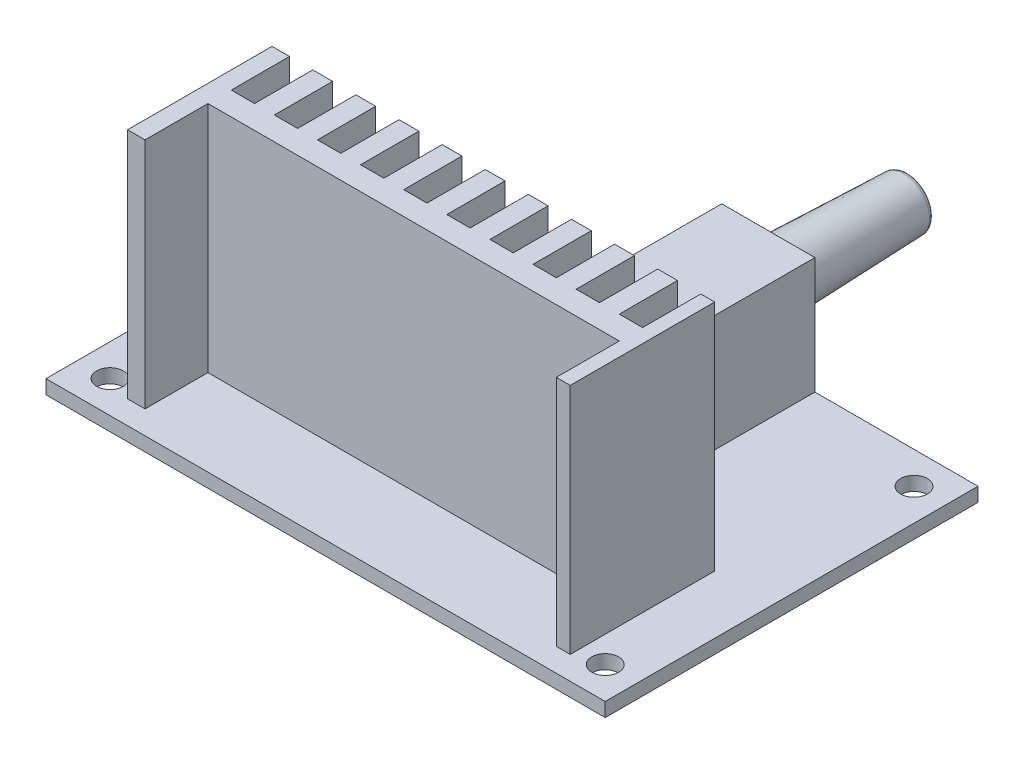
SolidWorks part; units mm, degrees
ref_plane "Front Plane" through (0, 0, 0) normal (0, 0, 1) x (1, 0, 0)
ref_plane "Top Plane" through (0, 0, 0) normal (0, 1, 0) x (1, 0, 0)
ref_plane "Right Plane" through (0, 0, 0) normal (1, 0, 0) x (0, 0, -1)
sketch "Sketch1" plane through (0, 0, 0) normal (0, 1, 0) x (1, 0, 0)
  line L1 (-30.48, -20.32) -> (30.48, -20.32)
  line L2 (-30.48, -20.32) -> (-30.48, 20.32)
  line L3 (-30.48, 20.32) -> (30.48, 20.32)
  line L4 (30.48, -20.32) -> (30.48, 20.32)
  line L5 (-30.48, -20.32) -> (30.48, 20.32) construction
  line L6 (-30.48, 20.32) -> (30.48, -20.32) construction
  point P0 (0, 0)
  dimension "D1" = 40.64
  dimension "D2" = 60.96
extrude "Boss-Extrude1" add sketch "Sketch1" along normal blind 1.524
sketch "Sketch2" plane through (0, 1.524, 0) normal (0, 1, 0) x (1, 0, 0)
  line L0 (-14.985, -2.032) -> (-14.985, -8.382)
  line L1 (-24.13, -17.78) -> (-22.225, -17.78)
  line L2 (-24.13, -17.78) -> (-24.13, -2.032)
  line L3 (-24.13, -2.032) -> (-22.225, -2.032)
  line L4 (24.13, -17.78) -> (24.13, -2.032)
  line L5 (-24.13, -17.78) -> (24.13, -2.032) construction
  line L6 (-24.13, -2.032) -> (24.13, -17.78) construction
  line L8 (-22.225, -2.032) -> (-22.225, -8.382)
  line L9 (-22.225, -8.382) -> (-19.685, -8.382)
  line L10 (-19.685, -2.032) -> (-19.685, -8.382)
  line L11 (-22.225, -2.032) -> (-19.685, -8.382) construction
  line L12 (-22.225, -8.382) -> (-19.685, -2.032) construction
  line L13 (-17.525, -8.382) -> (-14.985, -8.382)
  line L14 (-17.525, -2.032) -> (-17.525, -8.382)
  line L15 (-10.285, -2.032) -> (-10.285, -8.382)
  line L16 (-12.825, -8.382) -> (-10.285, -8.382)
  line L17 (-12.825, -2.032) -> (-12.825, -8.382)
  line L18 (-5.585, -2.032) -> (-5.585, -8.382)
  line L19 (-8.125, -8.382) -> (-5.585, -8.382)
  line L20 (-8.125, -2.032) -> (-8.125, -8.382)
  line L21 (-0.885, -2.032) -> (-0.885, -8.382)
  line L22 (-3.425, -8.382) -> (-0.885, -8.382)
  line L23 (-3.425, -2.032) -> (-3.425, -8.382)
  line L24 (3.815, -2.032) -> (3.815, -8.382)
  line L25 (1.275, -8.382) -> (3.815, -8.382)
  line L26 (1.275, -2.032) -> (1.275, -8.382)
  line L27 (8.515, -2.032) -> (8.515, -8.382)
  line L28 (5.975, -8.382) -> (8.515, -8.382)
  line L29 (5.975, -2.032) -> (5.975, -8.382)
  line L30 (13.215, -2.032) -> (13.215, -8.382)
  line L31 (10.675, -8.382) -> (13.215, -8.382)
  line L32 (10.675, -2.032) -> (10.675, -8.382)
  line L33 (17.915, -2.032) -> (17.915, -8.382)
  line L34 (15.375, -8.382) -> (17.915, -8.382)
  line L35 (15.375, -2.032) -> (15.375, -8.382)
  line L36 (22.615, -2.032) -> (22.615, -8.382)
  line L37 (20.075, -8.382) -> (22.615, -8.382)
  line L38 (20.075, -2.032) -> (20.075, -8.382)
  line L39 (-19.685, -2.032) -> (-17.525, -2.032)
  line L41 (-22.225, -17.78) -> (-22.225, -10.922)
  line L42 (-22.225, -10.922) -> (22.615, -10.922)
  line L43 (22.615, -17.78) -> (22.615, -10.922)
  line L44 (-22.225, -17.78) -> (22.615, -10.922) construction
  line L45 (-22.225, -10.922) -> (22.615, -17.78) construction
  line L46 (-14.985, -2.032) -> (-12.825, -2.032)
  line L47 (-10.285, -2.032) -> (-8.125, -2.032)
  line L48 (-5.585, -2.032) -> (-3.425, -2.032)
  line L49 (-0.885, -2.032) -> (1.275, -2.032)
  line L50 (3.815, -2.032) -> (5.975, -2.032)
  line L51 (8.515, -2.032) -> (10.675, -2.032)
  line L52 (13.215, -2.032) -> (15.375, -2.032)
  line L53 (17.915, -2.032) -> (20.075, -2.032)
  line L54 (22.615, -2.032) -> (24.13, -2.032)
  line L55 (22.615, -17.78) -> (24.13, -17.78)
  point P4 (0, -9.906)
  point P12 (-20.955, -5.207)
  point P13 (-16.255, -8.382)
  point P49 (-20.955, -8.382)
  point P54 (0.195, -14.351)
  dimension "D1" = 48.26
  dimension "D2" = 15.748
  dimension "D3" = 2.54
  dimension "D4" = 2.54
  dimension "D5" = 6.35
  dimension "D6" = 3.175
  dimension "D8" = 4.7
  dimension "D9" = 2.54
  dimension "D7" = 10
extrude "Boss-Extrude2" add sketch "Sketch2" along normal blind 25.4
sketch "Sketch3" plane through (0, 1.524, 0) normal (0, 1, 0) x (1, 0, 0)
  line L0 (-30.48, 20.32) -> (-30.48, -20.32) construction
  line L1 (30.48, 20.32) -> (-30.48, 20.32) construction
  line L2 (0, 0) -> (50000, 0) construction
  line L3 (0, 0) -> (0, -50000) construction
  circle A0 centre (-26.9945, 16.83) radius 1.4605
  circle A1 centre (26.9945, 16.83) radius 1.4605
  circle A2 centre (26.9945, -16.83) radius 1.4605
  circle A3 centre (-26.9945, -16.83) radius 1.4605
  dimension "D1" = 2.921
  dimension "D2" = 3.4855
  dimension "D3" = 3.49
extrude "Cut-Extrude1" cut sketch "Sketch3" against normal through all
sketch "Sketch4" plane through (0, 1.524, 0) normal (0, 1, 0) x (1, 0, 0)
  line L0 (30.48, -20.32) -> (30.48, 20.32) construction
  line L1 (2.54, 20.32) -> (12.7, 20.32)
  line L2 (2.54, 20.32) -> (2.54, 7.62)
  line L3 (2.54, 7.62) -> (12.7, 7.62)
  line L4 (12.7, 20.32) -> (12.7, 7.62)
  line L5 (2.54, 20.32) -> (12.7, 7.62) construction
  line L6 (2.54, 7.62) -> (12.7, 20.32) construction
  line L7 (30.48, 20.32) -> (-30.48, 20.32) construction
  point P4 (7.62, 13.97)
  dimension "D1" = 27.94
  dimension "D2" = 10.16
  dimension "D3" = 12.7
extrude "Boss-Extrude3" add sketch "Sketch4" along normal blind 12.7 separate body
sketch "Sketch5" plane through (0, 0, -20.32) normal (0, 0, -1) x (-1, 0, 0)
  circle A0 centre (-7.62, 9.3987) radius 3.3401
  dimension "D1" = 6.6802
extrude "Boss-Extrude4" add sketch "Sketch5" along normal blind 15.24 draft 2 separate body
fillet "Fillet1" radius 0.5 1 edges at (4.8121, 9.3987, -35.56)
